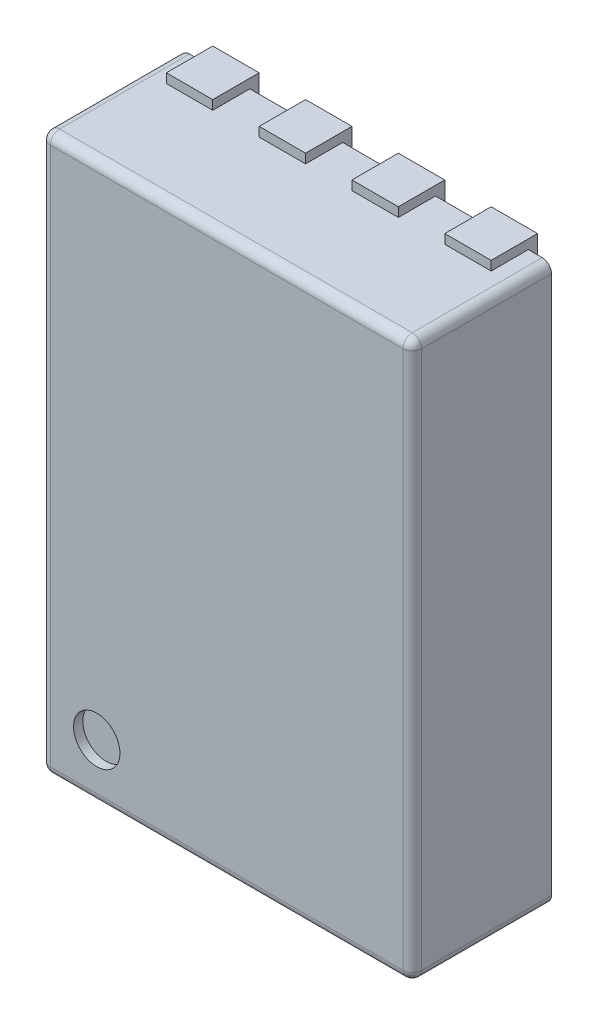
SolidWorks part; units mm, degrees
ref_plane "Front Plane" through (0, 0, 0) normal (0, 0, 1) x (1, 0, 0)
ref_plane "Top Plane" through (0, 0, 0) normal (0, 1, 0) x (1, 0, 0)
ref_plane "Right Plane" through (0, 0, 0) normal (1, 0, 0) x (0, 0, -1)
ref_plane "Plane1" through (0, 0, 0.08) normal (0, 0, 1) x (1, 0, 0)
sketch "Sketch1" plane through (0, 0, 0.08) normal (0, 0, 1) x (1, 0, 0)
  line L0 (0, 0) -> (4.4011, 0) construction
  line L1 (4.4011, 0) -> (0, 0) construction
  line L2 (0, 0) -> (0, 5.1455) construction
  line L4 (-1, 1.5) -> (1, 1.5)
  line L5 (-1, 1.5) -> (-1, -1.5)
  line L6 (-1, -1.5) -> (1, -1.5)
  line L7 (1, 1.5) -> (1, -1.5)
  dimension "D1" = 1.5
  dimension "D2" = 3
  dimension "D3" = 1
  dimension "D4" = 2
extrude "Extrude1" add sketch "Sketch1" along normal blind 0.75
sketch "Sketch2" plane through (0, 0, 0.83) normal (0, 0, 1) x (1, 0, 0)
  line L0 (-1, -1.5) -> (1, -1.5) construction
  line L1 (-1, 1.5) -> (-1, -1.5) construction
  circle A0 centre (-0.7, -1.2) radius 0.125
  point P2 (-0.5467, -1.0297)
  dimension "D1" = 0.25
  dimension "D3" = 0.3
  dimension "D2" = 0.3
extrude "Extrude2" cut sketch "Sketch2" against normal blind 0.05
fillet "Fillet1" radius 0.05 8 edges at (-1, -1.5, 0.455) (1, 1.5, 0.455) (0, -1.5, 0.83) (1, 0, 0.83) (1, -1.5, 0.455) (-1, 0, 0.83) (-1, 1.5, 0.455) (0, 1.5, 0.83)
ref_plane "Plane3" through (0.75, 0, 0) normal (1, 0, 0) x (0, 0, -1)
sketch "Sketch4" plane through (0.75, 0, 0) normal (1, 0, 0) x (0, 0, -1)
  line L0 (-0.28, -1.5) -> (-0.08, -1.5)
  line L1 (-0.08, -1.5) -> (-0.78, -1.5) construction
  line L2 (-0.08, -1.5) -> (-0.08, -1.2)
  line L3 (-0.08, -1.45) -> (-0.08, 1.45) construction
  dimension "D1" = 0.2
  dimension "D2" = 0.3
extrude "Extrude-Thin1" add sketch "Sketch4" along normal mid plane 0.25 separate body thin
sketch "Sketch5" plane through (0, 0, 0.08) normal (0, 0, -1) x (-1, 0, 0)
  line L1 (-0.73, 0.68) -> (0.73, 0.68)
  line L2 (-0.73, 0.68) -> (-0.73, -0.68)
  line L3 (0.73, -0.68) -> (0.73, 0.68)
  line L4 (-0.73, -0.68) -> (0.73, -0.68)
  line L5 (0, 0) -> (1.7545, 0) construction
  line L6 (0, 0) -> (0, 0.916) construction
  point P8 (0.73, -0.1874)
  point P10 (0.73, -0.129)
  point P11 (0.73, -0.0732)
  point P12 (0, 0)
  dimension "D2" = 0.73
  dimension "D3" = 0.68
extrude "Extrude4" add sketch "Sketch5" along normal blind 0.05
pattern_linear "LPattern2" count 4 spacing 0.5 along (-1, 0, 0) of "Extrude-Thin1"
mirror "Mirror1" about plane through (0, 0, 0) normal (0, 1, 0) of "LPattern2", "Extrude-Thin1"
